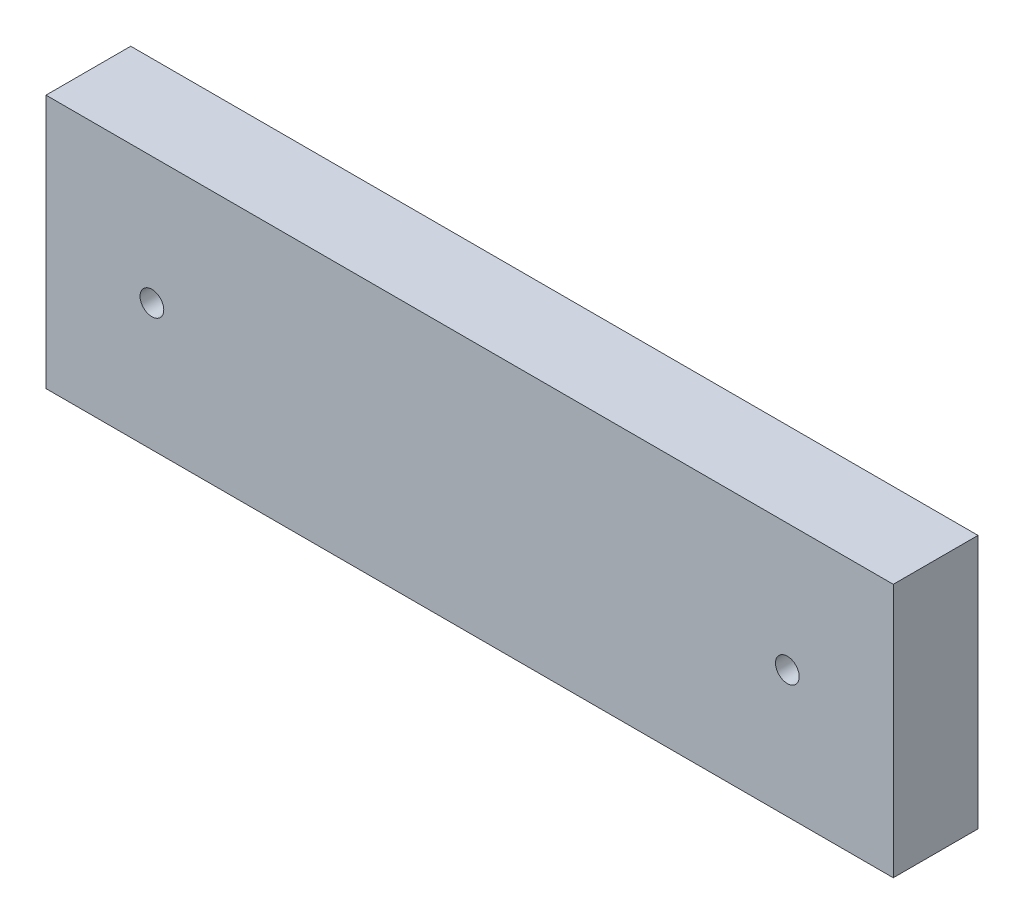
SolidWorks part; units mm, degrees
ref_plane "정면" through (0, 0, 0) normal (0, 0, 1) x (1, 0, 0)
ref_plane "윗면" through (0, 0, 0) normal (0, 1, 0) x (1, 0, 0)
ref_plane "우측면" through (0, 0, 0) normal (1, 0, 0) x (0, 0, -1)
sketch "스케치1" plane through (0, 0, 0) normal (0, 0, 1) x (1, 0, 0)
  line L0 (0, 15) -> (0, 0) construction
  line L1 (-50, 15) -> (50, 15)
  line L2 (-50, 15) -> (-50, -15)
  line L3 (-50, -15) -> (50, -15)
  line L4 (50, 15) -> (50, -15)
  line L5 (-50, 15) -> (50, -15) construction
  line L6 (-50, -15) -> (50, 15) construction
  line L7 (-37.5, 0) -> (0, 0) construction
  circle A0 centre (-37.5, 0) radius 1.4
  circle A1 centre (37.5, 0) radius 1.4
  point P0 (0, 0)
  dimension "D1" = 2.8
  dimension "D2" = 100
  dimension "D3" = 37.5
  dimension "D4" = 30
extrude "보스-돌출1" add sketch "스케치1" along normal blind 10
